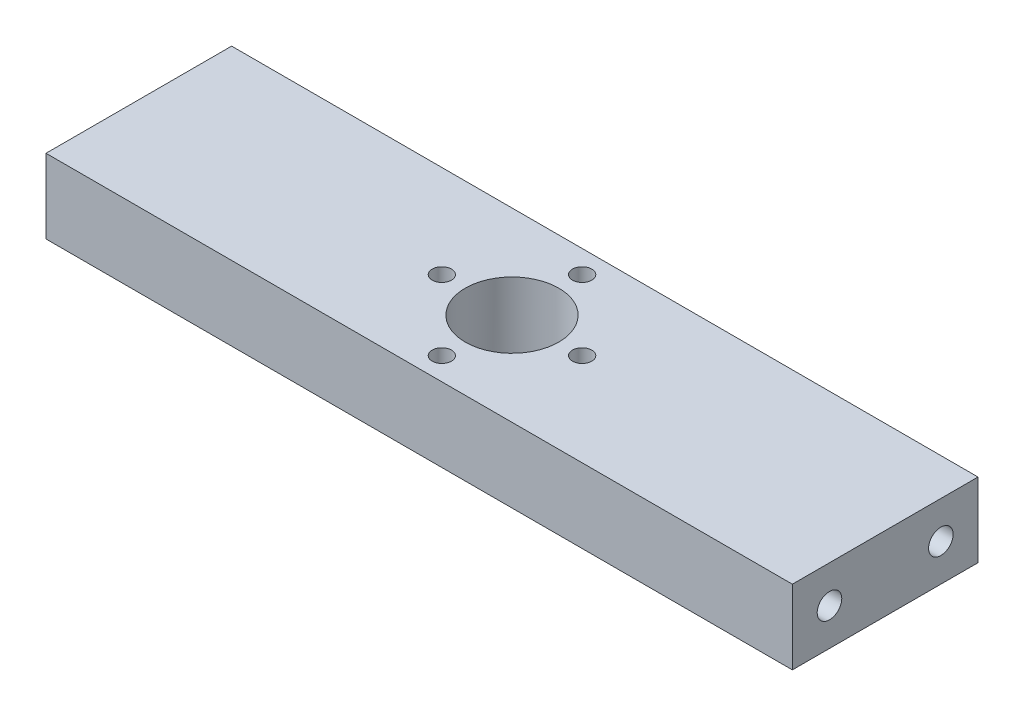
SolidWorks part; units mm, degrees
material "6061 Alloy"
ref_plane "Front" through (0, 0, 0) normal (0, 0, 1) x (1, 0, 0)
ref_plane "Top" through (0, 0, 0) normal (0, 1, 0) x (1, 0, 0)
ref_plane "Right" through (0, 0, 0) normal (1, 0, 0) x (0, 0, -1)
sketch "Sketch1" plane through (0, 0, 0) normal (0, 1, 0) x (1, 0, 0)
  line L1 (-63.83, -15.875) -> (63.83, -15.875)
  line L2 (-63.83, -15.875) -> (-63.83, 15.875)
  line L3 (-63.83, 15.875) -> (63.83, 15.875)
  line L4 (63.83, -15.875) -> (63.83, 15.875)
  line L5 (-63.83, -15.875) -> (63.83, 15.875) construction
  line L6 (-63.83, 15.875) -> (63.83, -15.875) construction
  point P0 (0, 0)
  dimension "D1" = 127.66
  dimension "D2" = 31.75
extrude "Boss-Extrude1" add sketch "Sketch1" along normal mid plane 12.7 contours L3 L4 L1 L2
hole_wizard "M5x0.8 Tapped Hole1" positions "Sketch2" profile "Sketch4" tap size "M5x0.8" standard "ANSI Metric"
sketch "Sketch2" plane through (-63.83, 0, 0) normal (-1, 0, 0) x (0, 0, 1)
  point P0 (9.525, 0)
  point P3 (-9.525, 0)
sketch "Sketch4" plane through (-63.83, 0, 9.525) normal (0, 1, 0) x (0, 0, 1)
  line L0 (0, 0) -> (0, 12.192)
  line L1 (0, 12.192) -> (2.1, 10.9302)
  line L2 (2.1, 10.9302) -> (2.1, 0)
  line L5 (2.1, 0) -> (0, 0)
  line L10 (0, 12.192) -> (-2.1, 10.9302) construction
  line L11 (0, -6.35) -> (0, 107.95) construction
  dimension "Tap Drill Dia." = 4.2
  dimension "Tap Drill Depth" = 12.192
  dimension "Drill Angle" = 118
cosmetic thread "Hole Thread1" parameters "D1"=9.906, "D2"=5
cosmetic thread "Hole Thread2" parameters "D1"=9.906, "D2"=5
mirror "Mirror1" about plane through (0, 0, 0) normal (1, 0, 0) of "M5x0.8 Tapped Hole1"
cosmetic thread "Hole Thread3" parameters "D1"=9.906, "D2"=5
cosmetic thread "Hole Thread4" parameters "D1"=9.906, "D2"=5
hole_wizard "Ø16.0mm Dowel Hole1" positions "Sketch6" profile "Sketch7" hole size "Ø16.0" standard "ANSI Metric" end condition up to next
sketch "Sketch6" plane through (0, 6.35, 0) normal (0, 1, 0) x (1, 0, 0)
  point P0 (0, 0)
sketch "Sketch7" plane through (0, 6.35, 0) normal (1, 0, 0) x (0, 0, 1)
  line L0 (0, 0) -> (0, 12.7)
  line L1 (0, 12.7) -> (8, 12.7)
  line L2 (8, 12.7) -> (8, 0)
  line L5 (8, 0) -> (0, 0)
  line L11 (0, -6.35) -> (0, 107.95) construction
  dimension "Thru Hole Dia." = 16
  dimension "Thru Hole Depth" = 12.7
sketch "Sketch8" plane through (0, 6.35, 0) normal (0, 1, 0) x (1, 0, 0)
  circle A0 centre (0, 0) radius 12 construction
  point P3 (0, 12)
  point P4 (-12, 0)
  point P5 (12, 0)
  point P6 (0, -12)
  dimension "D1" = 24
hole_wizard "Tap Drill for M4x0.7 Tap1" positions "Sketch9" profile "Sketch10" hole size "M4x0.7" standard "ANSI Metric" end condition up to next
sketch "Sketch9" plane through (0, 6.35, 0) normal (0, 1, 0) x (1, 0, 0)
  point P0 (0, 12)
  point P3 (12, 0)
  point P6 (-12, 0)
  point P9 (0, -12)
sketch "Sketch10" plane through (0, 6.35, -12) normal (1, 0, 0) x (0, 0, 1)
  line L0 (0, 0) -> (0, 12.7)
  line L1 (0, 12.7) -> (1.65, 12.7)
  line L2 (1.65, 12.7) -> (1.65, 0)
  line L5 (1.65, 0) -> (0, 0)
  line L11 (0, -6.35) -> (0, 107.95) construction
  dimension "Thru Hole Dia." = 3.3
  dimension "Thru Hole Depth" = 12.7
